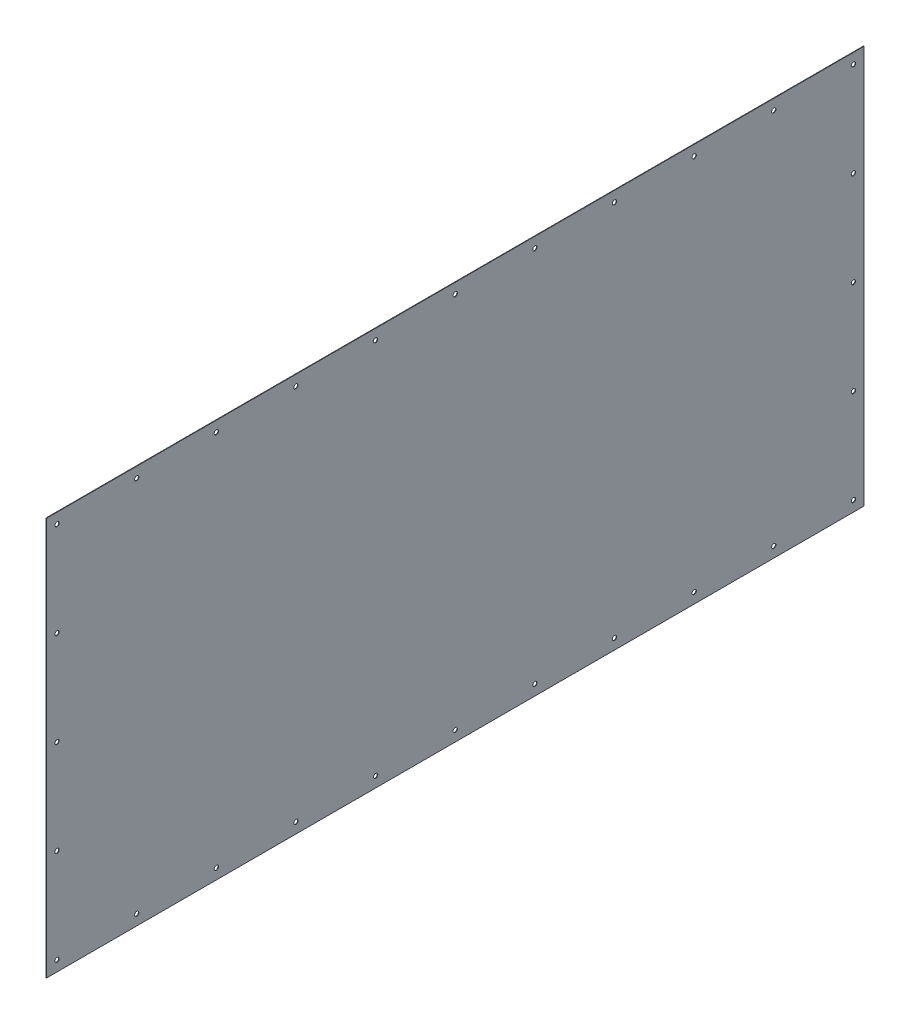
SolidWorks part; units mm, degrees
ref_plane "Front Plane" through (0, 0, 0) normal (0, 0, 1) x (1, 0, 0)
ref_plane "Top Plane" through (0, 0, 0) normal (0, 1, 0) x (1, 0, 0)
ref_plane "Right Plane" through (0, 0, 0) normal (1, 0, 0) x (0, 0, -1)
sketch "Sketch1" plane through (0, 0, 0) normal (1, 0, 0) x (0, 0, -1)
  line L0 (-759.96, 179.99) -> (759.96, 179.99) construction
  line L1 (-779.96, 379.98) -> (779.96, 379.98)
  line L2 (-779.96, 379.98) -> (-779.96, -379.98)
  line L3 (-779.96, -379.98) -> (779.96, -379.98)
  line L4 (779.96, 379.98) -> (779.96, -379.98)
  line L5 (-779.96, 379.98) -> (779.96, -379.98) construction
  line L6 (-779.96, -379.98) -> (779.96, 379.98) construction
  line L7 (-759.96, 359.98) -> (759.96, 359.98) construction
  line L8 (-759.96, 359.98) -> (-759.96, -359.98) construction
  line L9 (-759.96, -359.98) -> (759.96, -359.98) construction
  line L10 (759.96, 359.98) -> (759.96, -359.98) construction
  line L11 (-759.96, 359.98) -> (759.96, -359.98) construction
  line L12 (-759.96, -359.98) -> (759.96, 359.98) construction
  line L13 (759.96, 179.99) -> (-759.96, -179.99) construction
  line L14 (-759.96, -179.99) -> (759.96, -179.99) construction
  line L15 (-759.96, 0) -> (0, 0) construction
  line L16 (0, 179.99) -> (0, 0) construction
  line L17 (0, 0) -> (0, -179.99) construction
  line L18 (0, -179.99) -> (-0.01, -359.98) construction
  line L19 (-0.01, 359.98) -> (0, 179.99) construction
  circle A0 centre (-759.96, 359.98) radius 4.1
  circle A1 centre (-759.96, -359.98) radius 4.1
  circle A2 centre (-607.97, 359.98) radius 4.1
  circle A3 centre (-607.97, -359.98) radius 4.1
  circle A4 centre (-455.98, 359.98) radius 4.1
  circle A5 centre (-455.98, -359.98) radius 4.1
  circle A6 centre (-303.99, 359.98) radius 4.1
  circle A7 centre (-303.99, -359.98) radius 4.1
  circle A8 centre (-152, 359.98) radius 4.1
  circle A9 centre (-152, -359.98) radius 4.1
  circle A10 centre (-0.01, 359.98) radius 4.1
  circle A11 centre (-0.01, -359.98) radius 4.1
  circle A12 centre (151.98, 359.98) radius 4.1
  circle A13 centre (151.98, -359.98) radius 4.1
  circle A14 centre (303.97, 359.98) radius 4.1
  circle A15 centre (303.97, -359.98) radius 4.1
  circle A16 centre (455.96, 359.98) radius 4.1
  circle A17 centre (455.96, -359.98) radius 4.1
  circle A18 centre (607.95, 359.98) radius 4.1
  circle A19 centre (607.95, -359.98) radius 4.1
  circle A20 centre (759.94, 359.98) radius 4.1
  circle A21 centre (759.94, -359.98) radius 4.1
  circle A22 centre (-759.96, 179.99) radius 4.1
  circle A23 centre (-759.96, 0) radius 4.1
  circle A24 centre (-759.96, -179.99) radius 4.1
  circle A25 centre (759.96, 0) radius 4.1
  circle A26 centre (759.96, 179.99) radius 4.1
  circle A27 centre (759.96, -179.99) radius 4.1
  point P0 (0, 0)
  point P6 (0, 0)
  dimension "D5" = 8.2
  dimension "D1" = 1519.92
  dimension "D2" = 719.96
  dimension "D3" = 20
  dimension "D4" = 20
  dimension "D6" = 11
extrude "Boss-Extrude1" add sketch "Sketch1" along normal blind 1
